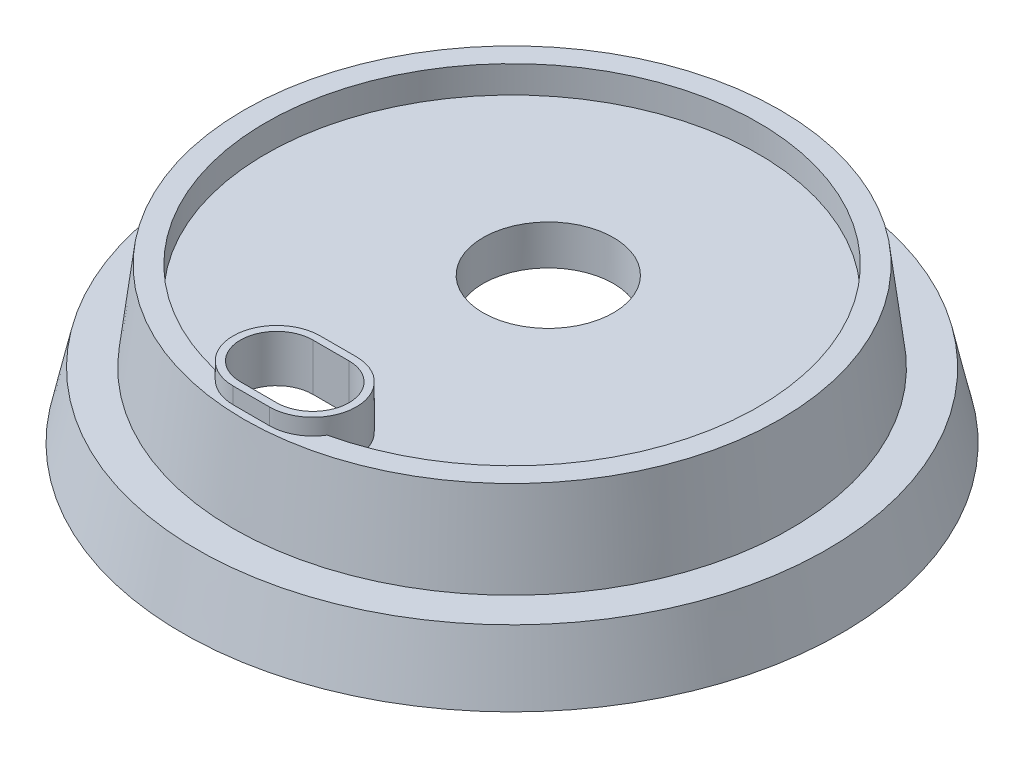
SolidWorks part; units mm, degrees
ref_plane "前视基准面" through (0, 0, 0) normal (0, 0, 1) x (1, 0, 0)
ref_plane "上视基准面" through (0, 0, 0) normal (0, 1, 0) x (1, 0, 0)
ref_plane "右视基准面" through (0, 0, 0) normal (1, 0, 0) x (0, 0, -1)
sketch "草图2" plane through (0, 0, 0) normal (0, 0, 1) x (1, 0, 0)
  line L0 (0, 0) -> (43.5, 0) construction
  line L1 (0, 0) -> (0, -9) construction
  line L2 (0, -9) -> (45.5, -9) construction
  line L3 (43.5, 0) -> (45.5, -9)
  line L4 (0, 0) -> (38.5, 0) construction
  line L5 (38.5, 0) -> (43.5, 0)
  line L6 (0, 0) -> (0, 12.3) construction
  line L7 (0, 12.3) -> (37, 12.3) construction
  line L8 (37, 12.3) -> (38.5, 0)
  line L9 (0, 12.3) -> (0, 8.55) construction
  line L10 (37, 12.3) -> (34, 12.3)
  line L11 (0, 8.55) -> (34, 8.55)
  line L12 (34, 8.55) -> (34, 12.3)
  line L13 (0, 8.05) -> (34.5, 8.05)
  line L14 (34.5, 8.05) -> (34.5, 11.8)
  line L15 (36.5573, 11.8) -> (34.5, 11.8)
  line L16 (36.5573, 11.8) -> (38.0573, -0.5)
  line L17 (38.0573, -0.5) -> (43.0989, -0.5)
  line L18 (43.0989, -0.5) -> (45.0119, -9.1085)
  line L19 (0, 8.55) -> (0, 8.05)
  line L20 (45.0119, -9.1085) -> (45.5, -9)
  dimension "D1" = 43.5
  dimension "D2" = 9
  dimension "D3" = 45.5
  dimension "D4" = 38.5
  dimension "D5" = 12.3
  dimension "D6" = 37
  dimension "D7" = 3.75
  dimension "D8" = 3
  dimension "D9" = 0.5
revolve "旋转1" add sketch "草图2" angle 360 about L6
sketch "草图4" plane through (0, 8.55, 0) normal (0, 1, 0) x (1, 0, 0)
  line L0 (0, -37) -> (0, -30) construction
  line L1 (-2.5, -30) -> (2.5, -30) construction
  line L2 (-2.5, -35) -> (2.5, -35)
  line L3 (-2.5, -25) -> (2.5, -25)
  circle A0 centre (0, 0) radius 37 construction
  arc A1 (2.5, -35) -> (2.5, -25) centre (2.5, -30) ccw
  arc A2 (-2.5, -35) -> (-2.5, -25) centre (-2.5, -30) cw
  point P8 (0, -30)
  dimension "D3" = 5
  dimension "D1" = 7
  dimension "D2" = 5
extrude "切除-拉伸1" cut sketch "草图4" against normal mid plane 10
sketch "草图6" plane through (0, 8.55, 0) normal (0, 1, 0) x (1, 0, 0)
  line L0 (-2.5, -35) -> (2.5, -35) construction
  line L1 (-2.5, -25) -> (2.5, -25)
  line L2 (-2.5, -35) -> (2.5, -35)
  line L3 (-2.5, -24) -> (2.5, -24)
  line L4 (-2.5, -36) -> (2.5, -36)
  arc A0 (2.5, -25) -> (2.5, -35) centre (2.5, -30) cw
  arc A1 (-2.5, -25) -> (-2.5, -35) centre (-2.5, -30) ccw
  arc A2 (-6.125, -33.4438) -> (-2.5, -35) centre (-2.5, -30) ccw construction
  arc A3 (2.5, -24) -> (2.5, -36) centre (2.5, -30) cw
  arc A4 (-2.5, -24) -> (-2.5, -36) centre (-2.5, -30) ccw
  dimension "D1" = 1
extrude "凸台-拉伸1" add sketch "草图6" along normal blind 6
sketch "草图8" plane through (0, 8.55, 0) normal (0, 1, 0) x (1, 0, 0)
  line L0 (0, 37) -> (0, 5) construction
  circle A0 centre (0, 0) radius 37 construction
  circle A1 centre (0, 5) radius 9
  dimension "D2" = 18
  dimension "D1" = 32
extrude "切除-拉伸2" cut sketch "草图8" against normal blind 6
sketch "草图9" plane through (0, 8.05, 0) normal (0, -1, 0) x (1, 0, 0)
  circle A1 centre (0, -5) radius 9
  circle A2 centre (0, -5) radius 10
  circle A3 centre (0, -5) radius 10
  dimension "D1" = 1
extrude "凸台-拉伸2" add sketch "草图9" along normal blind 5
